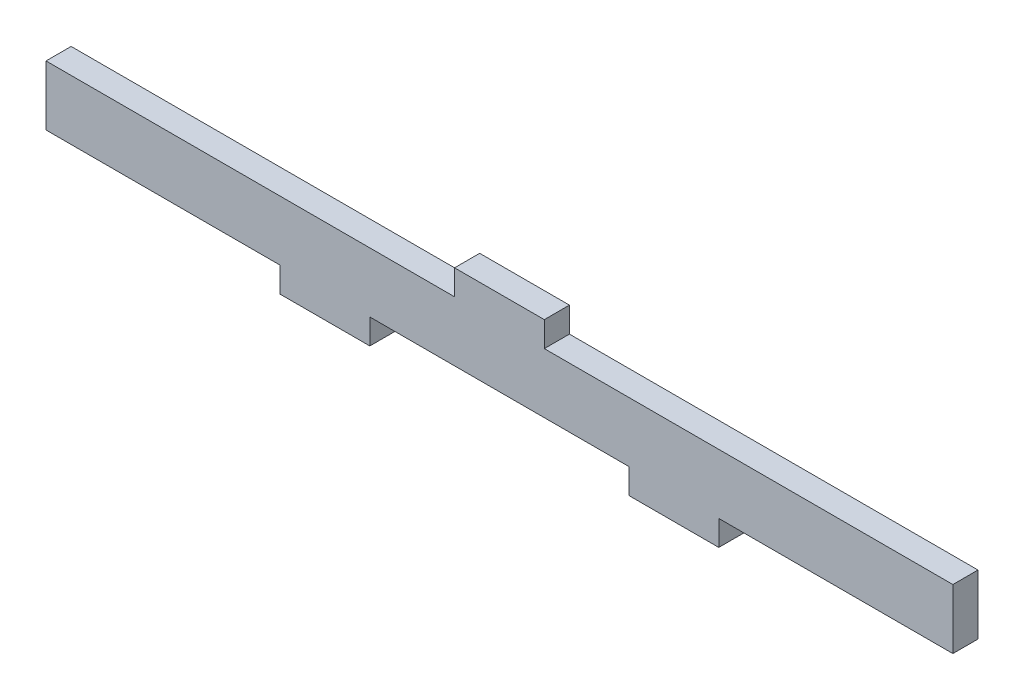
SolidWorks part; units mm, degrees
ref_plane "Front Plane" through (0, 0, 0) normal (0, 0, 1) x (1, 0, 0)
ref_plane "Top Plane" through (0, 0, 0) normal (0, 1, 0) x (1, 0, 0)
ref_plane "Right Plane" through (0, 0, 0) normal (1, 0, 0) x (0, 0, -1)
sketch "Sketch1" plane through (0, 0, 0) normal (0, 0, 1) x (1, 0, 0)
  line L1 (0, 0) -> (192.532, 0)
  line L2 (0, 0) -> (0, 23.368)
  line L3 (0, 23.368) -> (192.532, 23.368)
  line L4 (192.532, 0) -> (192.532, 23.368)
  dimension "D1" = 23.368
  dimension "D2" = 192.532
extrude "Boss-Extrude1" add sketch "Sketch1" along normal blind 5.334
sketch "Sketch2" plane through (0, 0, 5.334) normal (0, 0, 1) x (1, 0, 0)
  line L0 (0, 0) -> (192.532, 0) construction
  line L1 (0, 0) -> (49.6993, 0)
  line L2 (0, 0) -> (0, 5.334)
  line L3 (0, 5.334) -> (49.6993, 5.334)
  line L4 (49.6993, 0) -> (49.6993, 5.334)
  line L5 (68.7493, 0) -> (123.7827, 0)
  line L6 (68.7493, 0) -> (68.7493, 5.334)
  line L7 (68.7493, 5.334) -> (123.7827, 5.334)
  line L8 (123.7827, 0) -> (123.7827, 5.334)
  line L9 (49.6993, 5.334) -> (68.7493, 5.334) construction
  line L10 (192.532, 0) -> (142.8327, 0)
  line L11 (192.532, 0) -> (192.532, 5.334)
  line L12 (192.532, 5.334) -> (142.8327, 5.334)
  line L13 (142.8327, 0) -> (142.8327, 5.334)
  line L14 (123.7827, 5.334) -> (142.8327, 5.334) construction
  line L16 (86.741, 18.034) -> (105.791, 18.034) construction
  line L17 (0, 23.368) -> (86.741, 23.368)
  line L18 (0, 23.368) -> (0, 18.034)
  line L19 (0, 18.034) -> (86.741, 18.034)
  line L20 (86.741, 23.368) -> (86.741, 18.034)
  line L22 (192.532, 23.368) -> (105.791, 23.368)
  line L24 (192.532, 23.368) -> (192.532, 18.034)
  line L25 (192.532, 18.034) -> (105.791, 18.034)
  line L26 (105.791, 23.368) -> (105.791, 18.034)
  dimension "D1" = 19.05
  dimension "D2" = 5.334
  dimension "D3" = 19.05
  dimension "D4" = 55.0333
extrude "Cut-Extrude1" cut sketch "Sketch2" against normal through all
equation "\"material\"= \"gmaterial@full.assembly\""
equation "\"D1@Sketch1\"=(2*\"material\")+0.5"
equation "\"D2@Sketch1\"=8-(2*\"material\")"
equation "\"D1@Boss-Extrude1\"=\"material\""
equation "\"D2@Sketch2\"=\"material\""
equation "\"D4@Sketch2\"=(8-1.5)/3"
